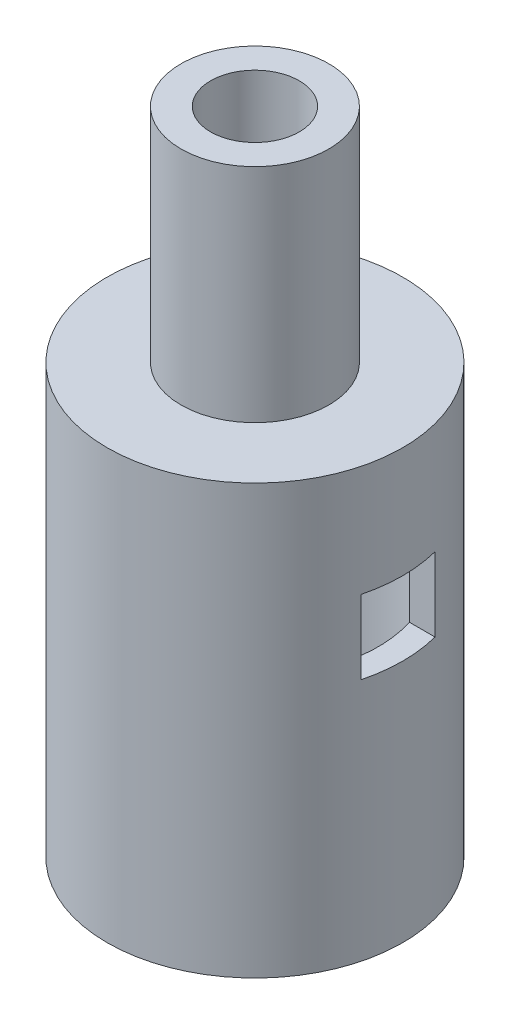
SolidWorks part; units mm, degrees
ref_plane "Front Plane" through (0, 0, 0) normal (0, 0, 1) x (1, 0, 0)
ref_plane "Top Plane" through (0, 0, 0) normal (0, 1, 0) x (1, 0, 0)
ref_plane "Right Plane" through (0, 0, 0) normal (1, 0, 0) x (0, 0, -1)
sketch "Sketch2" plane through (0, 0, 0) normal (0, 1, 0) x (1, 0, 0)
  circle A0 centre (0, 0) radius 7.62
  dimension "D1" = 15.24
extrude "Boss-Extrude1" add sketch "Sketch2" against normal blind 22.098 contours A0
sketch "Sketch3" plane through (0, -22.098, 0) normal (0, -1, 0) x (1, 0, 0)
  circle A0 centre (0, 0) radius 6.35
  dimension "D1" = 12.7
extrude "Cut-Extrude1" cut sketch "Sketch3" against normal blind 16.764
sketch "Sketch5" plane through (0, 0, 0) normal (0, 1, 0) x (1, 0, 0)
  circle A0 centre (0, 0) radius 2.3495
  dimension "D1" = 4.699
extrude "Cut-Extrude3" cut sketch "Sketch5" along normal blind 16.764 and the other way through all contours A0
sketch "Sketch6" plane through (0, 0, 0) normal (0, 1, 0) x (1, 0, 0)
  circle A0 centre (0, 0) radius 3.81
  dimension "D1" = 7.62
extrude "Boss-Extrude2" add sketch "Sketch6" along normal blind 11.43 contours A0
sketch "Sketch8" plane through (0, 11.43, 0) normal (0, 1, 0) x (1, 0, 0)
  circle A0 centre (0, 0) radius 2.286
  dimension "D1" = 4.572
extrude "Cut-Extrude4" cut sketch "Sketch8" against normal blind 11.176 contours A0
sketch "Sketch10" plane through (0, 0, 0) normal (0, -1, 0) x (1, 0, 0)
  circle A0 centre (0, 0) radius 1.7198
extrude "Cut-Extrude8" cut sketch "Sketch10" against normal up to next
sketch "Sketch12" plane through (0, 0, 0) normal (1, 0, 0) x (0, 0, -1)
  line L0 (7.62, 0) -> (-7.62, 0) construction
  line L1 (-1.905, -5.715) -> (1.905, -5.715)
  line L2 (-1.905, -5.715) -> (-1.905, -9.525)
  line L3 (-1.905, -9.525) -> (1.905, -9.525)
  line L4 (1.905, -5.715) -> (1.905, -9.525)
  line L5 (-1.905, -5.715) -> (1.905, -9.525) construction
  line L6 (-1.905, -9.525) -> (1.905, -5.715) construction
  point P0 (0, -7.62)
  point P5 (0, -8.3802)
  dimension "D1" = 3.81
  dimension "D2" = 3.81
  dimension "D3" = 7.62
extrude "Cut-Extrude10" cut sketch "Sketch12" against normal through all both and the other way through all
